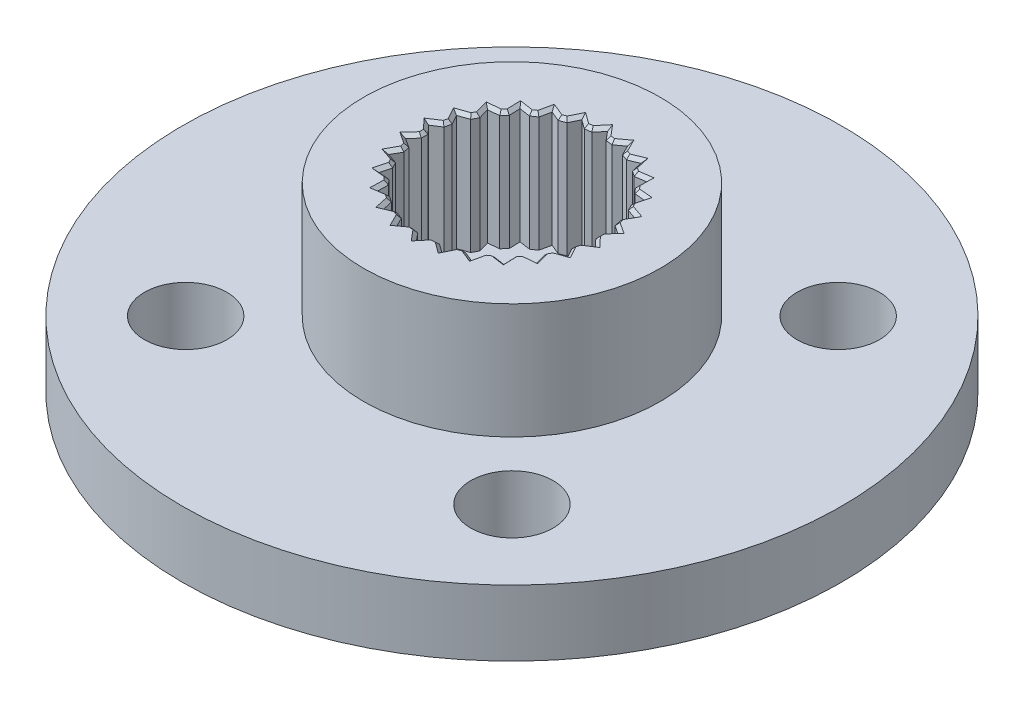
SolidWorks part; units mm, degrees
ref_plane "Front Plane" through (0, 0, 0) normal (0, 0, 1) x (1, 0, 0)
ref_plane "Top Plane" through (0, 0, 0) normal (0, 1, 0) x (1, 0, 0)
ref_plane "Right Plane" through (0, 0, 0) normal (1, 0, 0) x (0, 0, -1)
sketch "Sketch1" plane through (0, 0, 0) normal (0, 1, 0) x (1, 0, 0)
  line L0 (-4.9497, 4.9497) -> (4.9497, 4.9497) construction
  line L1 (4.9497, 4.9497) -> (4.9497, -4.9497) construction
  circle A0 centre (0, 0) radius 10
  circle A1 centre (-4.9497, 4.9497) radius 1.25
  circle A2 centre (4.9497, 4.9497) radius 1.25
  circle A3 centre (4.9497, -4.9497) radius 1.25
  circle A4 centre (-4.9497, -4.9497) radius 1.25
  circle A5 centre (0, 0) radius 7 construction
  circle A6 centre (0, 0) radius 1.5
  dimension "D1" = 20
  dimension "D2" = 2.5
  dimension "D3" = 3
  dimension "D4" = 14
extrude "Boss-Extrude1" add sketch "Sketch1" along normal blind 2
cosmetic thread "Cosmetic Thread1" parameters "D2"=3
cosmetic thread "Cosmetic Thread2" parameters "D2"=3
cosmetic thread "Cosmetic Thread3" parameters "D2"=3
cosmetic thread "Cosmetic Thread4" parameters "D2"=3
sketch "Sketch2" plane through (0, 2, 0) normal (0, 1, 0) x (1, 0, 0)
  circle A0 centre (0, 0) radius 4.5
  circle A1 centre (0, 0) radius 1.5 construction
  circle A2 centre (0, 0) radius 1.5
  dimension "D1" = 9
extrude "Boss-Extrude2" add sketch "Sketch2" along normal blind 3.5
sketch "Sketch3" plane through (0, 5.5, 0) normal (0, 1, 0) x (1, 0, 0)
  circle A0 centre (0, 0) radius 2.25
  dimension "D1" = 4.5
extrude "Cut-Extrude1" cut sketch "Sketch3" against normal blind 3.6
sketch "Sketch7" plane through (0, 5.5, 0) normal (0, 1, 0) x (1, 0, 0)
  line L0 (-1.035, 2.4395) -> (-0.843, 2.5123)
  line L1 (-0.843, 2.5123) -> (-0.7982, 2.6036)
  line L2 (-0.7982, 2.6036) -> (-0.694, 2.8157)
  line L3 (-0.694, 2.8157) -> (-0.5032, 2.6763)
  line L4 (-0.5032, 2.6763) -> (-0.4211, 2.6163)
  line L5 (-0.4211, 2.6163) -> (-0.2173, 2.6411)
  line L6 (-0.2173, 2.6411) -> (-0.1519, 2.719)
  line L7 (-0.1519, 2.719) -> (0, 2.9)
  line L8 (0, 2.9) -> (0.1519, 2.719)
  line L9 (0.1519, 2.719) -> (0.2173, 2.6411)
  line L10 (0.2173, 2.6411) -> (0.4211, 2.6163)
  line L11 (0.4211, 2.6163) -> (0.5032, 2.6763)
  line L12 (0.5032, 2.6763) -> (0.694, 2.8157)
  line L13 (0.694, 2.8157) -> (0.7982, 2.6036)
  line L14 (0.7982, 2.6036) -> (0.843, 2.5123)
  line L15 (0.843, 2.5123) -> (1.035, 2.4395)
  line L16 (1.035, 2.4395) -> (1.1291, 2.4781)
  line L17 (1.1291, 2.4781) -> (1.3477, 2.5678)
  line L18 (1.3477, 2.5678) -> (1.3981, 2.337)
  line L19 (1.3981, 2.337) -> (1.4197, 2.2376)
  line L20 (1.4197, 2.2376) -> (1.5887, 2.1209)
  line L21 (1.5887, 2.1209) -> (1.6893, 2.1359)
  line L22 (1.6893, 2.1359) -> (1.9231, 2.1707)
  line L23 (1.9231, 2.1707) -> (1.9167, 1.9345)
  line L24 (1.9167, 1.9345) -> (1.914, 1.8328)
  line L25 (1.914, 1.8328) -> (2.0501, 1.6791)
  line L26 (2.0501, 1.6791) -> (2.1514, 1.6696)
  line L27 (2.1514, 1.6696) -> (2.3867, 1.6474)
  line L28 (2.3867, 1.6474) -> (2.324, 1.4196)
  line L29 (2.324, 1.4196) -> (2.297, 1.3215)
  line L30 (2.297, 1.3215) -> (2.3924, 1.1397)
  line L31 (2.3924, 1.1397) -> (2.4884, 1.1062)
  line L32 (2.4884, 1.1062) -> (2.7115, 1.0284)
  line L33 (2.7115, 1.0284) -> (2.5962, 0.8221)
  line L34 (2.5962, 0.8221) -> (2.5465, 0.7334)
  line L35 (2.5465, 0.7334) -> (2.5956, 0.534)
  line L36 (2.6809, 0.4785) -> (2.5956, 0.534) construction
  line L37 (2.5956, 0.534) -> (2.6809, 0.4785)
  line L38 (2.6809, 0.4785) -> (2.8789, 0.3496)
  line L39 (2.6809, 0.4785) -> (2.8789, 0.3496)
  line L40 (2.7175, 0.177) -> (2.648, 0.1027)
  line L41 (2.648, 0.1027) -> (2.648, -0.1027)
  line L42 (2.648, -0.1027) -> (2.7175, -0.177)
  line L43 (2.7175, -0.177) -> (2.8789, -0.3496)
  line L44 (2.8789, -0.3496) -> (2.6809, -0.4785)
  line L45 (2.6809, -0.4785) -> (2.5956, -0.534)
  line L46 (2.5956, -0.534) -> (2.5465, -0.7334)
  line L47 (2.5465, -0.7334) -> (2.5962, -0.8221)
  line L48 (2.5962, -0.8221) -> (2.7115, -1.0284)
  line L49 (2.7115, -1.0284) -> (2.4884, -1.1062)
  line L50 (2.4884, -1.1062) -> (2.3924, -1.1397)
  line L51 (2.3924, -1.1397) -> (2.4884, -1.1062) construction
  line L52 (2.3924, -1.1397) -> (2.297, -1.3215)
  line L53 (2.297, -1.3215) -> (2.324, -1.4196)
  line L54 (2.324, -1.4196) -> (2.3867, -1.6474)
  line L55 (2.3867, -1.6474) -> (2.1514, -1.6696)
  line L56 (2.1514, -1.6696) -> (2.0501, -1.6791)
  line L57 (2.0501, -1.6791) -> (1.914, -1.8328)
  line L58 (1.914, -1.8328) -> (1.9167, -1.9345)
  line L59 (1.9167, -1.9345) -> (1.9231, -2.1707)
  line L60 (1.9231, -2.1707) -> (1.6893, -2.1359)
  line L61 (1.6893, -2.1359) -> (1.5887, -2.1209)
  line L62 (1.5887, -2.1209) -> (1.4197, -2.2376)
  line L63 (1.4197, -2.2376) -> (1.3981, -2.337)
  line L64 (1.3981, -2.337) -> (1.3477, -2.5678)
  line L65 (1.3477, -2.5678) -> (1.1291, -2.4781)
  line L66 (1.1291, -2.4781) -> (1.035, -2.4395)
  line L67 (1.035, -2.4395) -> (0.843, -2.5123)
  line L68 (0.843, -2.5123) -> (0.7982, -2.6036)
  line L69 (0.7982, -2.6036) -> (0.694, -2.8157)
  line L70 (0.694, -2.8157) -> (0.5032, -2.6763)
  line L71 (0.5032, -2.6763) -> (0.4211, -2.6163)
  line L72 (0.4211, -2.6163) -> (0.2173, -2.6411)
  line L73 (0.2173, -2.6411) -> (0.1519, -2.719)
  line L74 (0.1519, -2.719) -> (0, -2.9)
  line L75 (0, -2.9) -> (-0.1519, -2.719)
  line L76 (-0.1519, -2.719) -> (-0.2173, -2.6411)
  line L77 (-0.2173, -2.6411) -> (-0.4211, -2.6163)
  line L78 (-0.4211, -2.6163) -> (-0.5032, -2.6763)
  line L79 (-0.5032, -2.6763) -> (-0.694, -2.8157)
  line L80 (-0.694, -2.8157) -> (-0.7982, -2.6036)
  line L81 (-0.7982, -2.6036) -> (-0.843, -2.5123)
  line L82 (-0.843, -2.5123) -> (-1.035, -2.4395)
  line L83 (-1.035, -2.4395) -> (-1.1291, -2.4781)
  line L84 (-1.1291, -2.4781) -> (-1.3477, -2.5678)
  line L85 (-1.3477, -2.5678) -> (-1.3981, -2.337)
  line L86 (-1.3981, -2.337) -> (-1.4197, -2.2376)
  line L87 (-1.4197, -2.2376) -> (-1.5887, -2.1209)
  line L88 (-1.5887, -2.1209) -> (-1.6893, -2.1359)
  line L89 (-1.6893, -2.1359) -> (-1.9231, -2.1707)
  line L90 (-1.9231, -2.1707) -> (-1.9167, -1.9345)
  line L91 (-1.9167, -1.9345) -> (-1.914, -1.8328)
  line L92 (-1.914, -1.8328) -> (-2.0501, -1.6791)
  line L93 (-2.0501, -1.6791) -> (-2.1514, -1.6696)
  line L94 (-2.1514, -1.6696) -> (-2.3867, -1.6474)
  line L95 (-2.3867, -1.6474) -> (-2.324, -1.4196)
  line L96 (-2.324, -1.4196) -> (-2.297, -1.3215)
  line L97 (-2.297, -1.3215) -> (-2.3924, -1.1397)
  line L98 (-2.3924, -1.1397) -> (-2.4884, -1.1062)
  line L99 (-2.4884, -1.1062) -> (-2.7115, -1.0284)
  line L100 (-2.7115, -1.0284) -> (-2.5962, -0.8221)
  line L101 (-2.5962, -0.8221) -> (-2.5465, -0.7334)
  line L102 (-2.5465, -0.7334) -> (-2.5956, -0.534)
  line L103 (-2.5956, -0.534) -> (-2.6809, -0.4785)
  line L104 (-2.6809, -0.4785) -> (-2.8789, -0.3496)
  line L105 (-2.8789, -0.3496) -> (-2.7175, -0.177)
  line L106 (-2.7175, -0.177) -> (-2.648, -0.1027)
  line L107 (-2.648, -0.1027) -> (-2.648, 0.1027)
  line L108 (-2.648, 0.1027) -> (-2.7175, 0.177)
  line L109 (-2.7175, 0.177) -> (-2.8789, 0.3496)
  line L110 (-2.8789, 0.3496) -> (-2.6809, 0.4785)
  line L111 (-2.6809, 0.4785) -> (-2.5956, 0.534)
  line L112 (-2.5956, 0.534) -> (-2.5465, 0.7334)
  line L113 (-2.5465, 0.7334) -> (-2.5962, 0.8221)
  line L114 (-2.5962, 0.8221) -> (-2.7115, 1.0284)
  line L115 (-2.7115, 1.0284) -> (-2.4884, 1.1062)
  line L116 (-2.4884, 1.1062) -> (-2.3924, 1.1397)
  line L117 (-2.3924, 1.1397) -> (-2.297, 1.3215)
  line L118 (-2.297, 1.3215) -> (-2.324, 1.4196)
  line L119 (-2.324, 1.4196) -> (-2.3867, 1.6474)
  line L120 (-2.3867, 1.6474) -> (-2.1514, 1.6696)
  line L121 (-2.1514, 1.6696) -> (-2.0501, 1.6791)
  line L122 (-2.0501, 1.6791) -> (-1.914, 1.8328)
  line L123 (-1.914, 1.8328) -> (-1.9167, 1.9345)
  line L124 (-1.9167, 1.9345) -> (-1.9231, 2.1707)
  line L125 (-1.9231, 2.1707) -> (-1.6893, 2.1359)
  line L126 (-1.6893, 2.1359) -> (-1.5887, 2.1209)
  line L127 (-1.5887, 2.1209) -> (-1.4197, 2.2376)
  line L128 (-1.4197, 2.2376) -> (-1.3981, 2.337)
  line L129 (-1.3981, 2.337) -> (-1.3477, 2.5678)
  line L130 (-1.3477, 2.5678) -> (-1.1291, 2.4781)
  line L131 (-1.1291, 2.4781) -> (-1.035, 2.4395)
  line L132 (-0.843, 2.5123) -> (-0.7982, 2.6036)
  line L133 (-0.694, 2.8157) -> (-0.5032, 2.6763)
  line L134 (-0.4211, 2.6163) -> (-0.2173, 2.6411)
  line L135 (-0.1519, 2.719) -> (0, 2.9)
  line L136 (0.1519, 2.719) -> (0.2173, 2.6411)
  line L137 (0.4211, 2.6163) -> (0.5032, 2.6763)
  line L138 (0.694, 2.8157) -> (0.7982, 2.6036)
  line L139 (1.035, 2.4395) -> (1.3477, 2.5678)
  line L140 (1.3981, 2.337) -> (1.4197, 2.2376)
  line L141 (1.5887, 2.1209) -> (1.6893, 2.1359)
  line L142 (1.9231, 2.1707) -> (1.9167, 1.9345)
  line L143 (1.914, 1.8328) -> (2.0501, 1.6791)
  line L144 (2.1514, 1.6696) -> (2.3867, 1.6474)
  line L145 (2.324, 1.4196) -> (2.297, 1.3215)
  line L146 (2.3924, 1.1397) -> (2.7115, 1.0284)
  line L147 (2.5962, 0.8221) -> (2.5465, 0.7334)
  line L148 (2.8789, 0.3496) -> (2.7175, 0.177)
extrude "Cut-Extrude2" cut sketch "Sketch7" against normal up to surface (3.6 mm away) contours L148 L38 L37 L35 L34 L33 L32 L31 L30 L29 L28 L27 L26 L25 L24 L23 L22 L21 L20 L19 L18 L17 L16 L15 L14 L13 L12 L11 L10 L9 L8 L7 L6 L5 L4 L3 L2 L1 L0 L131 L130 L129 L128 L127 L126 L125 L124 L123 L122 L121 L120 up to face at (0, 1.9, 1.5)
chamfer "Chamfer1" distance 0.1 angle 45 78 edges at (-2.629, 5.5, -0.8809) (-2.5711, 5.5, -0.6337) (-2.7372, 5.5, -0.4418) (-2.7634, 5.5, -0.2261) (-2.648, 5.5, 0) (-2.7634, 5.5, 0.2261) (-2.7372, 5.5, 0.4418) (-2.5711, 5.5, 0.6337) (-2.629, 5.5, 0.8809) (-2.552, 5.5, 1.084) (-2.3447, 5.5, 1.2306) (-2.3418, 5.5, 1.4844) (-2.2184, 5.5, 1.6632) (-1.9821, 5.5, 1.756) (-1.9185, 5.5, 2.0017) (-1.7559, 5.5, 2.1458) (-1.5042, 5.5, 2.1793) (-1.3837, 5.5, 2.4027) (-1.1913, 5.5, 2.5037) (-0.939, 5.5, 2.4759) (-0.7685, 5.5, 2.664) (-0.5576, 5.5, 2.716) (-0.3192, 5.5, 2.6287) (-0.1086, 5.5, 2.7705) (0.1086, 5.5, 2.7705) (0.3192, 5.5, 2.6287) (0.5576, 5.5, 2.716) (0.7685, 5.5, 2.664) (0.939, 5.5, 2.4759) (1.1913, 5.5, 2.5037) (1.3837, 5.5, 2.4027) (1.5042, 5.5, 2.1793) (1.7559, 5.5, 2.1458) (1.9185, 5.5, 2.0017) (1.9821, 5.5, 1.756) (2.2184, 5.5, 1.6632) (2.3418, 5.5, 1.4844) (2.3447, 5.5, 1.2306) (2.552, 5.5, 1.084) (2.629, 5.5, 0.8809) (2.5711, 5.5, 0.6337) (2.7372, 5.5, 0.4418) (2.7634, 5.5, 0.2261) (2.648, 5.5, 0) (2.7634, 5.5, -0.2261) (2.7372, 5.5, -0.4418) (2.5711, 5.5, -0.6337) (2.629, 5.5, -0.8809) (2.552, 5.5, -1.084) (2.3447, 5.5, -1.2306) (2.3418, 5.5, -1.4844) (2.2184, 5.5, -1.6632) (1.9821, 5.5, -1.756) (1.9185, 5.5, -2.0017) (1.7559, 5.5, -2.1458) (1.5042, 5.5, -2.1793) (1.3837, 5.5, -2.4027) (1.1913, 5.5, -2.5037) (0.939, 5.5, -2.4759) (0.7685, 5.5, -2.664) (0.5576, 5.5, -2.716) (0.3192, 5.5, -2.6287) (0.1086, 5.5, -2.7705) (-0.1086, 5.5, -2.7705) (-0.3192, 5.5, -2.6287) (-0.5576, 5.5, -2.716) (-0.7685, 5.5, -2.664) (-0.939, 5.5, -2.4759) (-1.1913, 5.5, -2.5037) (-1.3837, 5.5, -2.4027) (-1.5042, 5.5, -2.1793) (-1.7559, 5.5, -2.1458) (-1.9185, 5.5, -2.0017) (-1.9821, 5.5, -1.756) (-2.2184, 5.5, -1.6632) (-2.3418, 5.5, -1.4844) (-2.3447, 5.5, -1.2306) (-2.552, 5.5, -1.084)
